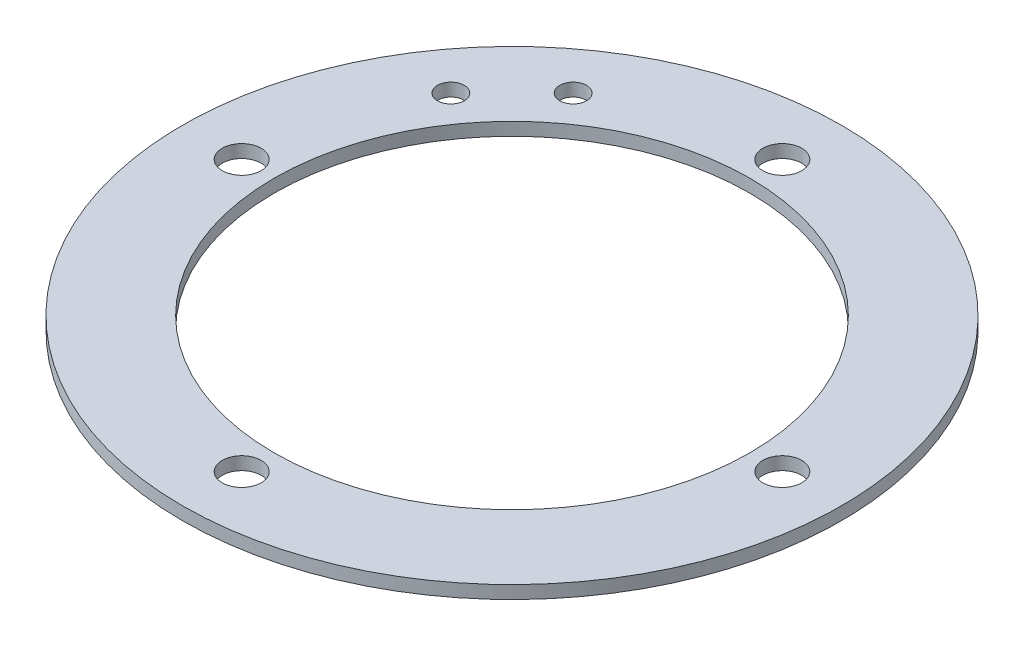
SolidWorks part; units mm, degrees
ref_plane "Front Plane" through (0, 0, 0) normal (0, 0, 1) x (1, 0, 0)
ref_plane "Top Plane" through (0, 0, 0) normal (0, 1, 0) x (1, 0, 0)
ref_plane "Right Plane" through (0, 0, 0) normal (1, 0, 0) x (0, 0, -1)
sketch "Sketch1" plane through (0, 0, 0) normal (0, 1, 0) x (1, 0, 0)
  line L0 (0, 76.2) -> (0, 62.5) construction
  line L1 (0, 62.5) -> (0, 55) construction
  circle A0 centre (0, 0) radius 76.2
  circle A1 centre (0, 0) radius 62.5 construction
  circle A2 centre (0, 62.5) radius 4.5
  circle A3 centre (62.5, 0) radius 4.5
  circle A4 centre (0, -62.5) radius 4.5
  circle A5 centre (-62.5, 0) radius 4.5
  circle A6 centre (0, 0) radius 55
  point P15 (0, 0)
  dimension "D1" = 152.4
  dimension "D2" = 125
  dimension "D3" = 9
  dimension "D5" = 7.5
  dimension "D4" = 4
extrude "Boss-Extrude1" add sketch "Sketch1" along normal blind 3 contours A0
sketch "Sketch2" plane through (0, 3, 0) normal (0, 1, 0) x (1, 0, 0)
  line L0 (-51.6188, 37.4767) -> (-37.4767, 51.6188) construction
  line L1 (-44.5477, 44.5477) -> (0, 0) construction
  line L2 (-76.2, 0) -> (0, 0) construction
  circle A0 centre (-51.6188, 37.4767) radius 3.1
  circle A1 centre (-37.4767, 51.6188) radius 3.1
  circle A2 centre (0, 0) radius 76.2 construction
  dimension "D3" = 6.2
  dimension "D1" = 20
  dimension "D2" = 45
  dimension "D4" = 63
extrude "Cut-Extrude1" cut sketch "Sketch2" against normal blind 3 contours A1
